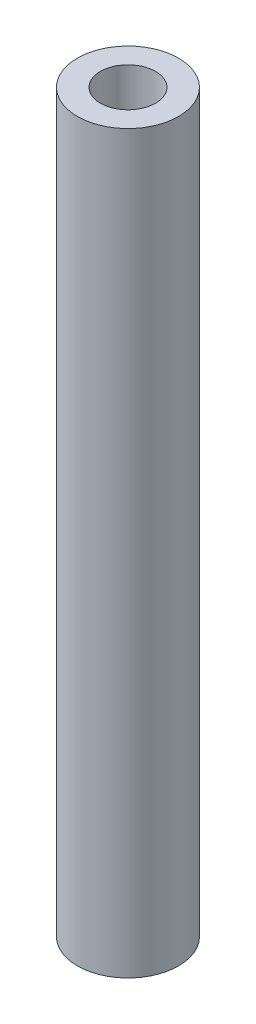
SolidWorks part; units mm, degrees
material "1060 Alloy"
ref_plane "Front" through (0, 0, 0) normal (0, 0, 1) x (1, 0, 0)
ref_plane "Top" through (0, 0, 0) normal (0, 1, 0) x (1, 0, 0)
ref_plane "Right" through (0, 0, 0) normal (1, 0, 0) x (0, 0, -1)
sketch "Sketch1" plane through (0, 0, 0) normal (0, 1, 0) x (1, 0, 0)
  circle A0 centre (0, 0) radius 2.75
  circle A1 centre (0, 0) radius 1.5
  dimension "D1" = 5.5
  dimension "D2" = 3
extrude "Boss-Extrude1" add sketch "Sketch1" along normal blind 40
